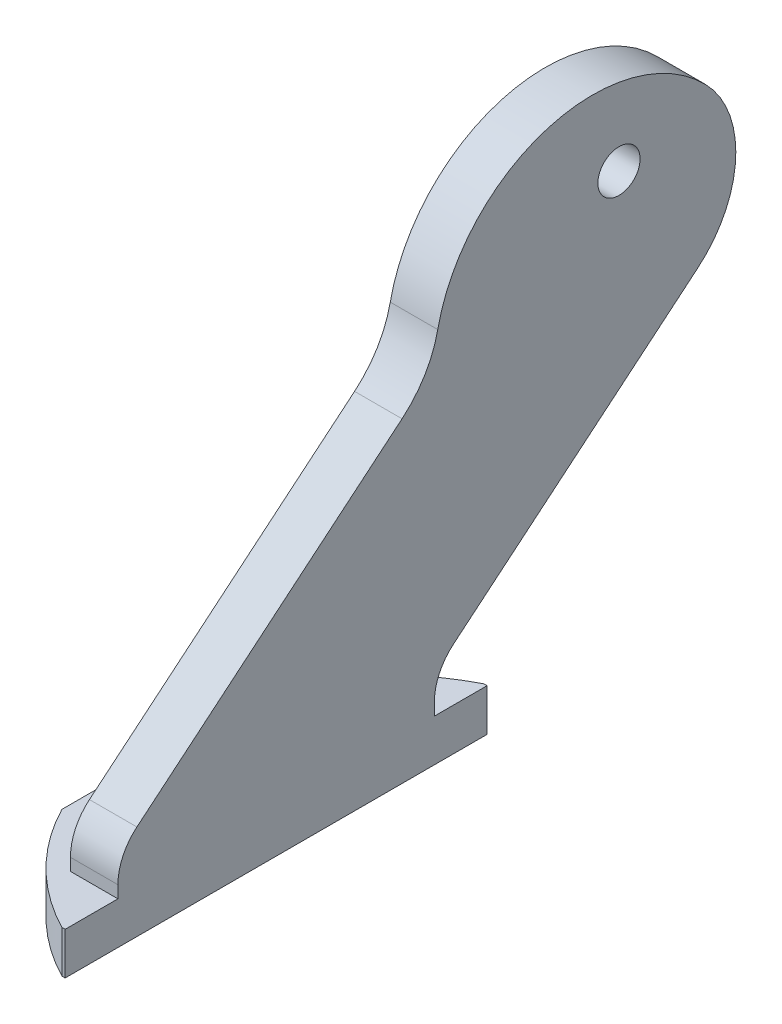
SolidWorks part; units mm, degrees
ref_plane "Alzado" through (0, 0, 0) normal (0, 0, 1) x (1, 0, 0)
ref_plane "Planta" through (0, 0, 0) normal (0, 1, 0) x (1, 0, 0)
ref_plane "Vista lateral" through (0, 0, 0) normal (1, 0, 0) x (0, 0, -1)
sketch "Croquis1" plane through (0, 0, 0) normal (0, 1, 0) x (1, 0, 0)
  line L1 (0, 40) -> (-20, 40)
  line L2 (-20, 40) -> (-20, -40)
  line L6 (-20, -40) -> (0, -40)
  line L7 (0, 40) -> (0, -40)
extrude "Saliente-Extruir2" add sketch "Croquis1" along normal blind 8
sketch "Croquis2" plane through (0, 8, 0) normal (0, 1, 0) x (1, 0, 0)
  line L0 (-20, 0) -> (20, 0) construction
  line L1 (-20, 40) -> (-20, -40) construction
  line L3 (-20, 40) -> (0, 40)
  line L4 (-20, 40) -> (-20, -40)
  line L5 (-20, -40) -> (0, -40)
  line L6 (0, 40) -> (0, -40)
  circle A0 centre (20, 0) radius 45
  line M8 (-20, 40) -> (-20, -40)
  line M9 (-20, -40) -> (0, -40)
extrude "Cortar-Extruir1" cut sketch "Croquis2" against normal blind 8 contours A0 M8 M9 | A0 L3 M8
sketch "Croquis4" plane through (0, 0, 0) normal (1, 0, 0) x (0, 0, -1)
  line L0 (0, 0) -> (30, 0)
  line L1 (-40, 0) -> (40, 0) construction
  line L2 (0, 0) -> (-30, 0)
  line L3 (-30, 0) -> (-30, 10.3163)
  line L4 (30, 0) -> (30, 10.3163)
  line L5 (0, 0) -> (0, 80) construction
  line L6 (0, 80) -> (65, 80) construction
  line L8 (90, 80) -> (90, 95) construction
  line L9 (90, 95) -> (30, 95) construction
  line L10 (30, 95) -> (30, 65) construction
  line L11 (30, 65) -> (90, 65) construction
  line L12 (90, 65) -> (90, 80) construction
  line L13 (23.8662, 59.8885) -> (-26.4018, 17.9985)
  line L14 (79.953, 56.6275) -> (33.5982, 17.9985)
  circle A0 centre (65, 80) radius 4
  arc A1 (30.6375, 71.1518) -> (81.448, 85.9758) centre (60, 65) cw
  arc A2 (23.8662, 59.8885) -> (30.6375, 71.1518) centre (11.0625, 75.2529) ccw
  arc A3 (79.953, 56.6275) -> (81.448, 85.9758) centre (67.1493, 71.9919) ccw
  arc A4 (30, 10.3163) -> (33.5982, 17.9985) centre (40, 10.3163) cw
  arc A5 (-30, 10.3163) -> (-26.4018, 17.9985) centre (-20, 10.3163) cw
  dimension "D1" = 20
  dimension "D2" = 10
extrude "Saliente-Extruir3" add sketch "Croquis4" against normal blind 13
ref_plane "Plano1" through (0, 95, 0) normal (0, 1, 0) x (1, 0, 0)
sketch "Croquis5" plane through (0, 95, 0) normal (0, 1, 0) x (1, 0, 0)
  line L0 (-20, 0) -> (-9, 0) construction
  line L1 (-20, 20.6155) -> (-20, -20.6155) construction
  line L2 (0, 87.1493) -> (-13, 87.1493) construction
  line L3 (-9, 87.1493) -> (-20, 87.1493)
  line L4 (-9, 87.1493) -> (-9, -46.6166)
  line L5 (-9, -46.6166) -> (-20, -46.6166)
  line L6 (-20, 87.1493) -> (-20, -46.6166)
extrude "Cortar-Extruir2" cut sketch "Croquis5" against normal blind 87
sketch "Croquis6" plane through (0, 8, 0) normal (0, 1, 0) x (1, 0, 0)
  line L0 (-20, 0) -> (-9, 0) construction
  line L1 (-20, 20.6155) -> (-20, -20.6155) construction
  line L2 (-9, -30) -> (-9, 30) construction
  line L3 (-14.5, 0) -> (-14.5, -28.892) construction
  line L4 (-14.5, 0) -> (-14.5, 28.892) construction
  arc A0 (-20, -20.6155) -> (-0.6155, -40) centre (20, 0) ccw construction
  arc A1 (-0.6155, 40) -> (-20, 20.6155) centre (20, 0) ccw construction
  circle A2 centre (-14.5, 14.446) radius 1.6
  circle A3 centre (-14.5, 0) radius 1.6
  circle A4 centre (-14.5, -14.446) radius 1.6
extrude "Cortar-Extruir3" cut sketch "Croquis6" against normal blind 87
sketch "Croquis7" plane through (0, 8, 0) normal (0, 1, 0) x (1, 0, 0)
  circle A0 centre (-14.5, 14.446) radius 3.25
  circle A1 centre (-14.5, 0) radius 3.25
  circle A2 centre (-14.5, -14.446) radius 3.25
extrude "Cortar-Extruir4" cut sketch "Croquis7" against normal blind 3
